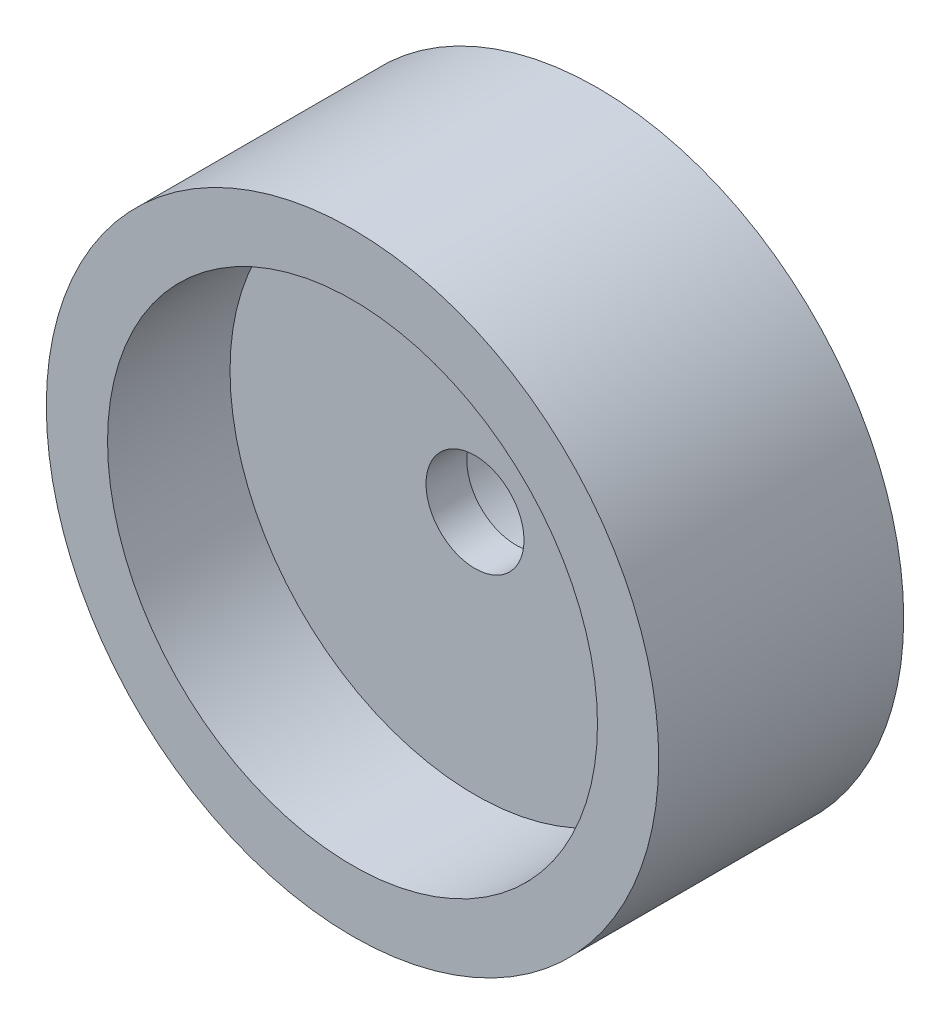
SolidWorks part; units mm, degrees
ref_plane "정면" through (0, 0, 0) normal (0, 0, 1) x (1, 0, 0)
ref_plane "윗면" through (0, 0, 0) normal (0, 1, 0) x (1, 0, 0)
ref_plane "우측면" through (0, 0, 0) normal (1, 0, 0) x (0, 0, -1)
sketch "스케치1" plane through (0, 0, 0) normal (0, 0, 1) x (1, 0, 0)
  circle A0 centre (0, 0) radius 7.5
  dimension "D1" = 15
extrude "보스-돌출1" add sketch "스케치1" along normal blind 6 contours A0
sketch "스케치2" plane through (0, 0, 6) normal (0, 0, 1) x (1, 0, 0)
  circle A0 centre (0, 0) radius 6
  dimension "D1" = 12
extrude "컷-돌출1" cut sketch "스케치2" against normal blind 3
hole_wizard "M2 소켓 머리 캡 나사용 카운터보어2" positions "스케치7" profile "스케치8" counterbore size "M2" standard "KS"
sketch "스케치7" plane through (0, 0, 0) normal (0, 0, -1) x (-1, 0, 0)
  point P0 (0, 0)
sketch "스케치8" plane through (0, 0, 0) normal (1, 0, 0) x (0, 1, 0)
  line L0 (0, 0) -> (0, 5.721)
  line L1 (0, 5.721) -> (1.2, 5)
  line L2 (1.2, 5) -> (1.2, 2)
  line L3 (1.2, 2) -> (2.25, 2)
  line L5 (2.25, 2) -> (2.25, 0.025)
  line L6 (2.25, 0.025) -> (2.275, 0)
  line L7 (2.275, 0) -> (0, 0)
  line L8 (-2.25, 0.025) -> (-2.275, 0) construction
  line L10 (0, 5.721) -> (-1.2, 5) construction
  line L11 (0, -6.35) -> (0, 107.95) construction
  dimension "구멍 지름" = 2.4
  dimension "구멍 깊이" = 5
  dimension "카운터보어 지름" = 4.5
  dimension "카운터보어 깊이" = 2
  dimension "표면 카운터싱크 지름" = 4.55
  dimension "표면 카운터싱크 각도" = 90
  dimension "드릴 각도" = 118
